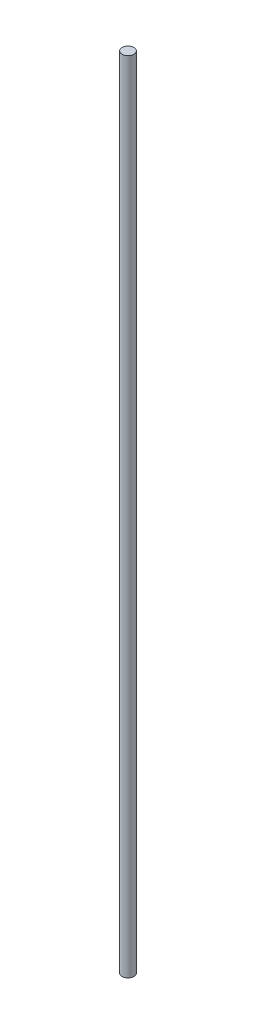
SolidWorks part; units mm, degrees
ref_plane "Front Plane" through (0, 0, 0) normal (0, 0, 1) x (1, 0, 0)
ref_plane "Top Plane" through (0, 0, 0) normal (0, 1, 0) x (1, 0, 0)
ref_plane "Right Plane" through (0, 0, 0) normal (1, 0, 0) x (0, 0, -1)
sketch "Sketch1" plane through (0, 0, 0) normal (0, 1, 0) x (1, 0, 0)
  circle A0 centre (0, 0) radius 1.5
  dimension "D1" = 3
extrude "Boss-Extrude1" add sketch "Sketch1" along normal blind 202
